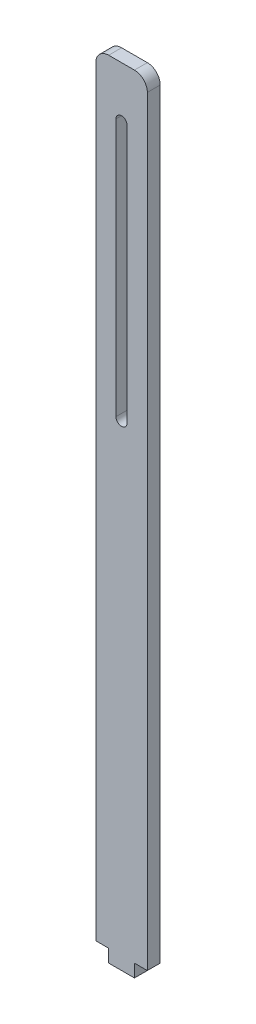
SolidWorks part; units mm, degrees
material "Pin"
ref_plane "Front" through (0, 0, 0) normal (0, 0, 1) x (1, 0, 0)
ref_plane "Top" through (0, 0, 0) normal (0, 1, 0) x (1, 0, 0)
ref_plane "Right" through (0, 0, 0) normal (1, 0, 0) x (0, 0, -1)
sketch "Esquisse2" plane through (0, 0, 0) normal (0, 0, 1) x (1, 0, 0)
  line L0 (6.35, -190.5) -> (12.7, -190.5)
  line L1 (-12.7, 190.5) -> (12.7, 190.5)
  line L2 (-12.7, 190.5) -> (-12.7, -190.5)
  line L3 (-12.7, -190.5) -> (-6.35, -190.5)
  line L4 (12.7, 190.5) -> (12.7, -190.5)
  line L5 (-12.7, 190.5) -> (12.7, -190.5) construction
  line L6 (-12.7, -190.5) -> (12.7, 190.5) construction
  line L8 (-6.35, -190.5) -> (-6.35, -196.85)
  line L9 (-6.35, -196.85) -> (6.35, -196.85)
  line L10 (6.35, -190.5) -> (6.35, -196.85)
  point P0 (0, 0)
  point P10 (-6.35, -193.675)
  dimension "D1" = 381
  dimension "D2" = 25.4
  dimension "D3" = 6.35
  dimension "D4" = 6.35
  dimension "D5" = 6.35
extrude "Boss.-Extru.1" add sketch "Esquisse2" along normal blind 6.35
sketch "Esquisse4" plane through (0, 0, 6.35) normal (0, 0, 1) x (1, 0, 0)
  line L0 (0, 165.1) -> (0, 38.1) construction
  line L1 (2.75, 165.1) -> (2.75, 38.1)
  line L2 (-2.75, 165.1) -> (-2.75, 38.1)
  line L3 (6.35, -190.5) -> (12.7, -190.5) construction
  arc A0 (2.75, 165.1) -> (-2.75, 165.1) centre (0, 165.1) ccw
  arc A1 (-2.75, 38.1) -> (2.75, 38.1) centre (0, 38.1) ccw
  point P3 (0, 101.6)
  dimension "D1" = 228.6
  dimension "D2" = 127
  dimension "D3" = 5.5
extrude "Enlèv. mat.-Extru.2" cut sketch "Esquisse4" against normal through all
fillet "Congé1" radius 6.35 2 edges at (-12.7, 190.5, 3.175) (12.7, 190.5, 3.175)
